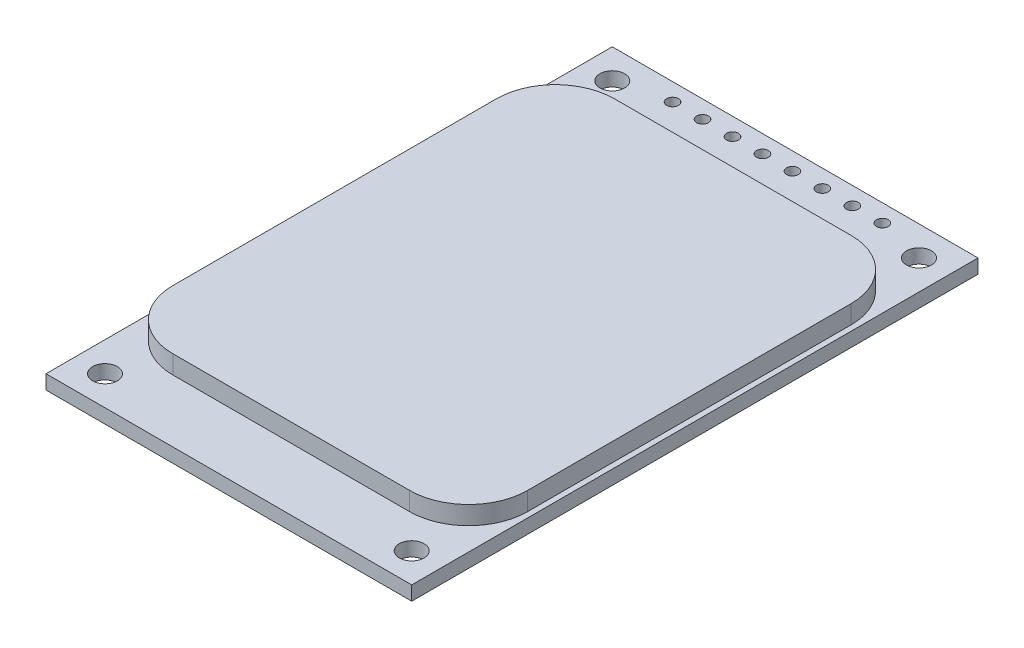
SolidWorks part; units mm, degrees
ref_plane "前视基准面" through (0, 0, 0) normal (0, 0, 1) x (1, 0, 0)
ref_plane "上视基准面" through (0, 0, 0) normal (0, 1, 0) x (1, 0, 0)
ref_plane "右视基准面" through (0, 0, 0) normal (1, 0, 0) x (0, 0, -1)
other "Configuration Table"
sketch "草图1" plane through (0, 0, 0) normal (0, 1, 0) x (1, 0, 0)
  line L1 (0, 0) -> (31, 0)
  line L2 (0, 0) -> (0, -48)
  line L3 (0, -48) -> (31, -48)
  line L4 (31, 0) -> (31, -48)
  dimension "D1" = 31
  dimension "D2" = 48
extrude "凸台-拉伸1" add sketch "草图1" along normal blind 1.2
sketch "草图2" plane through (0, 1.2, 0) normal (0, 1, 0) x (1, 0, 0)
  line L0 (15.5, 0) -> (15.5, -48) construction
  line L1 (31, 0) -> (0, 0) construction
  line L2 (0, -48) -> (31, -48) construction
  line L3 (0, -24) -> (31, -24) construction
  line L4 (0, 0) -> (0, -48) construction
  line L5 (31, -48) -> (31, 0) construction
  circle A0 centre (2.5, -2.5) radius 1.05
  circle A1 centre (28.5, -2.5) radius 1.05
  circle A2 centre (2.5, -45.5) radius 1.05
  circle A3 centre (28.5, -45.5) radius 1.05
  point P20 (0, 0)
  point P21 (26.5254, -45.5)
  point P22 (0, 0)
  point P23 (0, 0)
  dimension "D1" = 26
  dimension "D2" = 43
  dimension "D3" = 2.1
extrude "切除-拉伸1" cut sketch "草图2" against normal up to next
sketch "草图3" plane through (0, 1.2, 0) normal (0, 1, 0) x (1, 0, 0)
  line L0 (15.5, 0) -> (15.5, -48) construction
  line L1 (31, 0) -> (0, 0) construction
  line L2 (0, -48) -> (31, -48) construction
  circle A0 centre (14.23, -1.5) radius 0.5
  circle A1 centre (2.5, -2.5) radius 1.05 construction
  circle A2 centre (11.69, -1.5) radius 0.5
  circle A3 centre (9.15, -1.5) radius 0.5
  circle A4 centre (6.61, -1.5) radius 0.5
  circle A5 centre (24.39, -1.5) radius 0.5
  circle A6 centre (21.85, -1.5) radius 0.5
  circle A7 centre (19.31, -1.5) radius 0.5
  circle A8 centre (16.77, -1.5) radius 0.5
  point P10 (0, 0)
  dimension "D1" = 1
  dimension "D2" = 1.27
  dimension "D3" = 1
  dimension "D5" = 2.54
  dimension "D4" = 4
extrude "切除-拉伸2" cut sketch "草图3" against normal up to next
sketch "草图4" plane through (0, 1.2, 0) normal (0, 1, 0) x (1, 0, 0)
  line L0 (0, -24) -> (31, -24) construction
  line L1 (0.465, -5.285) -> (30.535, -5.285)
  line L2 (0.465, -5.285) -> (0.465, -42.715)
  line L3 (0.465, -42.715) -> (30.535, -42.715)
  line L4 (30.535, -5.285) -> (30.535, -42.715)
  line L5 (0, 0) -> (0, -48) construction
  line L6 (31, -48) -> (31, 0) construction
  line L7 (15.5, 0) -> (15.5, -48) construction
  line L8 (31, 0) -> (0, 0) construction
  line L9 (0, -48) -> (31, -48) construction
  dimension "D1" = 30.07
  dimension "D2" = 37.43
extrude "凸台-拉伸2" add sketch "草图4" along normal blind 1.56
fillet "圆角1" radius 5 4 edges at (0.465, 1.98, 42.715) (30.535, 1.98, 42.715) (30.535, 1.98, 5.285) (0.465, 1.98, 5.285)
